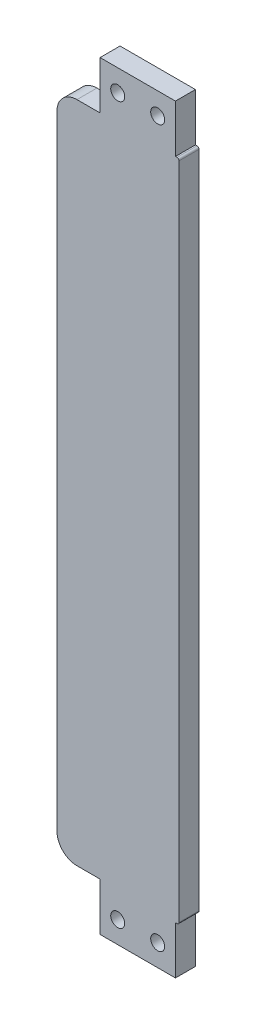
SolidWorks part; units mm, degrees
ref_plane "Front Plane" through (0, 0, 0) normal (0, 0, 1) x (1, 0, 0)
ref_plane "Top Plane" through (0, 0, 0) normal (0, 1, 0) x (1, 0, 0)
ref_plane "Right Plane" through (0, 0, 0) normal (1, 0, 0) x (0, 0, -1)
sketch "Sketch1" plane through (0, 0, 0) normal (0, 0, 1) x (1, 0, 0)
  line L0 (-20.1941, -20) -> (-20.1941, -176)
  line L1 (-9.4138, -15) -> (-15.1941, -15)
  line L2 (-9.4466, -181) -> (-15.1941, -181)
  line L12 (9.4466, -3) -> (-9.4138, -3)
  line L13 (-9.4138, -3) -> (-9.4138, -15)
  line L14 (9.4466, -15) -> (9.8466, -15)
  line L15 (9.4466, -15) -> (9.4466, -3)
  line L20 (10.3466, -15.5) -> (10.3466, -180.5)
  line L24 (-9.4466, -193) -> (9.4466, -193)
  line L25 (9.4466, -193) -> (9.4466, -181)
  line L26 (9.8466, -181) -> (9.4466, -181)
  line L27 (-9.4466, -181) -> (-9.4466, -193)
  circle A1 centre (-5, -187.5703) radius 1.75
  circle A2 centre (5, -187.5703) radius 1.75
  circle A3 centre (-5, -8.4297) radius 1.75
  circle A4 centre (5, -8.4297) radius 1.75
  arc A5 (9.8466, -15) -> (10.3466, -15.5) centre (9.8466, -15.5) cw
  arc A6 (10.3466, -180.5) -> (9.8466, -181) centre (9.8466, -180.5) cw
  arc A7 (-15.1941, -15) -> (-20.1941, -20) centre (-15.1941, -20) ccw
  arc A8 (-15.1941, -181) -> (-20.1941, -176) centre (-15.1941, -176) cw
  point P20 (10.3466, -15)
  point P23 (10.3466, -181)
  dimension "D1" = 3.5
  dimension "D2" = 3.5
  dimension "D3" = 3.5
  dimension "D4" = 3.5
  dimension "D7" = 0.5
  dimension "D8" = 0.5
  dimension "D9" = 5
  dimension "D10" = 5
  dimension "D5" = 0.9
  dimension "D6" = 0.9
extrude "Boss-Extrude1" add sketch "Sketch1" along normal blind 5
